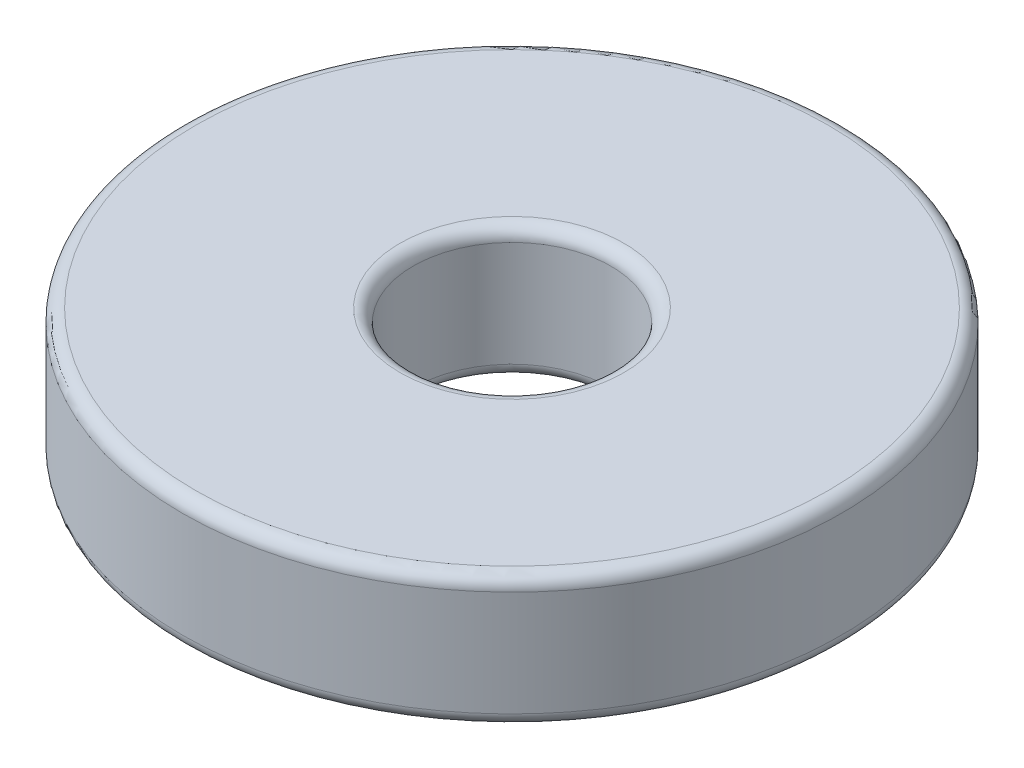
SolidWorks part; units mm, degrees
ref_plane "Front Plane" through (0, 0, 0) normal (0, 0, 1) x (1, 0, 0)
ref_plane "Top Plane" through (0, 0, 0) normal (0, 1, 0) x (1, 0, 0)
ref_plane "Right Plane" through (0, 0, 0) normal (1, 0, 0) x (0, 0, -1)
sketch "Sketch1" plane through (0, 0, 0) normal (0, 1, 0) x (1, 0, 0)
  circle A0 centre (0, 0) radius 25
  circle A1 centre (0, 0) radius 7.5
  dimension "D1" = 50
  dimension "D2" = 15
extrude "Boss-Extrude1" add sketch "Sketch1" along normal mid plane 10
fillet "Fillet1" radius 1 4 edges at (0, -5, 7.5) (0, -5, 25) (0, 5, 7.5) (0, 5, 25)
